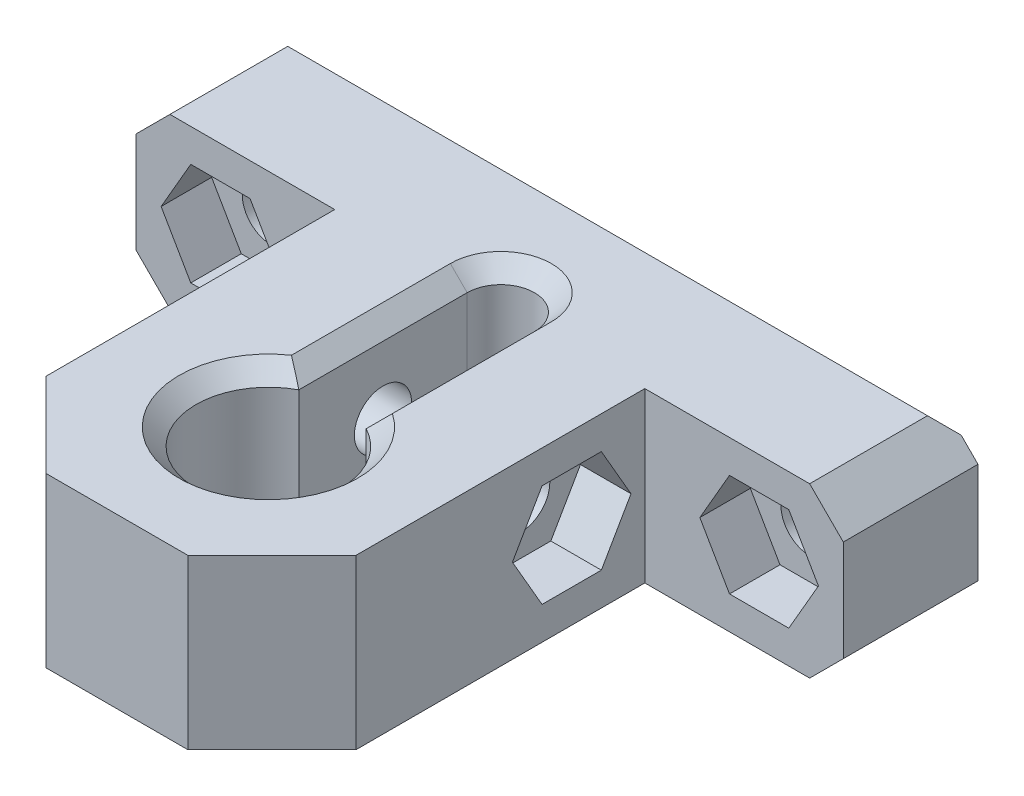
SolidWorks part; units mm, degrees
ref_plane "Front" through (0, 0, 0) normal (0, 0, 1) x (1, 0, 0)
ref_plane "Top" through (0, 0, 0) normal (0, 1, 0) x (1, 0, 0)
ref_plane "Right" through (0, 0, 0) normal (1, 0, 0) x (0, 0, -1)
sketch "Sketch1" plane through (0, 0, 0) normal (0, 1, 0) x (1, 0, 0)
  line L0 (-21, 0) -> (21, 0)
  line L1 (21, 0) -> (21, -8)
  line L2 (21, -8) -> (9.21, -8)
  line L3 (9.21, -8) -> (9.21, -30.15)
  line L4 (9.21, -30.15) -> (-9.21, -30.15)
  line L5 (-9.21, -30.15) -> (-9.21, -8)
  line L6 (-9.21, -8) -> (-21, -8)
  line L7 (-21, -8) -> (-21, 0)
  line L8 (0, 3.4386) -> (0, -31.4754) construction
  line L9 (-2, -7.3434) -> (-2, -17.3434)
  line L10 (2, -7.3434) -> (2, -17.3434)
  arc A0 (-2, -17.3434) -> (2, -17.3434) centre (0, -21.15) ccw
  arc A1 (-2, -7.3434) -> (2, -7.3434) centre (0, -7.3434) cw
  dimension "D2" = 8.6
  dimension "D4" = 9
  dimension "D1" = 42
  dimension "D3" = 30.15
  dimension "D5" = 8
  dimension "D6" = 4
  dimension "D7" = 10
  dimension "D8" = 18.42
extrude "Boss-Extrude1" add sketch "Sketch1" along normal blind 10
chamfer "Chamfer1" distance 5 angle 45 2 edges at (-9.21, 5, 30.15) (9.21, 5, 30.15)
chamfer "Chamfer2" distance 2 angle 45 4 edges at (21, 0, 4) (21, 10, 4) (-21, 0, 4) (-21, 10, 4)
chamfer "Chamfer3" distance 1 angle 45 10 edges at (2, 0, 12.3434) (0, 0, 5.3434) (0, 0, 25.45) (-2, 0, 12.3434) (2, 10, 12.3434) (0, 10, 5.3434) (0, 10, 25.45) (-2, 10, 12.3434) (0, 0, 0) (0, 10, 0)
sketch "Sketch2" plane through (9.21, 0, 0) normal (1, 0, 0) x (0, 0, -1)
  line L1 (-10.5825, 1.95) -> (-8.8216, 5)
  line L2 (-8.8216, 5) -> (-10.5825, 8.05)
  line L3 (-10.5825, 8.05) -> (-14.1043, 8.05)
  line L4 (-14.1043, 8.05) -> (-15.8653, 5)
  line L5 (-15.8653, 5) -> (-14.1043, 1.95)
  line L6 (-14.1043, 1.95) -> (-10.5825, 1.95)
  line L7 (-25.15, 10) -> (-8, 10) construction
  line L8 (-12.3434, 10) -> (-12.3434, 0) construction
  line L9 (-25.15, 0) -> (-8, 0) construction
  circle A0 centre (-12.3434, 5) radius 3.05 construction
  dimension "D1" = 6.1
extrude "Cut-Extrude1" cut sketch "Sketch2" against normal blind 3
hole_wizard "CBORE for M3 Hex Socket Head Cap Screw1" positions "Sketch5" profile "Sketch6" counterbore size "M3" standard "DIN" end condition through all
sketch "Sketch5" plane through (-9.21, 0, 0) normal (-1, 0, 0) x (0, 0, 1)
  line L1 (12.3434, 11.9144) -> (12.3434, -1.7687) construction
  line L5 (10.459, 5) -> (12.6378, 5) construction
  point P0 (12.3434, 5)
sketch "Sketch6" plane through (-9.21, 5, 12.3434) normal (0, 1, 0) x (0, 0, 1)
  line L0 (0, 0) -> (0, 30.21)
  line L1 (0, 30.21) -> (1.7, 30.21)
  line L3 (1.7, 30.21) -> (1.7, 3.4)
  line L4 (3.25, 3.4) -> (1.7, 3.4)
  line L5 (3.25, 3.4) -> (3.25, 0.025)
  line L6 (3.25, 0.025) -> (3.275, 0)
  line L7 (3.275, 0) -> (0, 0)
  line L8 (-3.25, 0.025) -> (-3.275, 0) construction
  line L11 (0, -6.35) -> (0, 107.95) construction
  dimension "Thru Hole Dia." = 3.4
  dimension "Thru Hole Depth" = 30.21
  dimension "C'Bore Dia." = 6.5
  dimension "C'Bore Depth" = 3.4
  dimension "Near C'Sink Dia." = 6.55
  dimension "Near C'Sink Angle" = 90
hole_wizard "M3 Clearance Hole1" positions "Sketch11" profile "Sketch10" hole size "M3" standard "DIN" end condition through all
sketch "Sketch11" plane through (0, 0, 0) normal (0, 0, -1) x (-1, 0, 0)
  line L2 (18.9892, 5) -> (11.5744, 5) construction
  line L4 (-19, 10) -> (19, 10) construction
  line L5 (19, 0) -> (-19, 0) construction
  line L6 (0, 12.2377) -> (0, -3.0724) construction
  point P0 (16, 5)
  point P20 (-16, 5)
  dimension "D1" = 32
sketch "Sketch10" plane through (-16, 5, 0) normal (1, 0, 0) x (0, 1, 0)
  line L0 (0, 0) -> (0, 30.15)
  line L1 (0, 30.15) -> (1.7, 30.15)
  line L2 (1.7, 30.15) -> (1.7, 0)
  line L5 (1.7, 0) -> (0, 0)
  line L11 (0, -6.35) -> (0, 107.95) construction
  dimension "Thru Hole Dia." = 3.4
  dimension "Thru Hole Depth" = 30.15
sketch "Sketch9" plane through (0, 0, 8) normal (0, 0, -1) x (-1, 0, 0)
  line L0 (0, 13.8123) -> (0, -4.7083) construction
  line L1 (17.7609, 1.95) -> (19.5218, 5)
  line L2 (19.5218, 5) -> (17.7609, 8.05)
  line L3 (17.7609, 8.05) -> (14.2391, 8.05)
  line L4 (14.2391, 8.05) -> (12.4782, 5)
  line L5 (12.4782, 5) -> (14.2391, 1.95)
  line L6 (14.2391, 1.95) -> (17.7609, 1.95)
  line L7 (-14.2391, 1.95) -> (-17.7609, 1.95)
  line L8 (-12.4782, 5) -> (-14.2391, 1.95)
  line L9 (-14.2391, 8.05) -> (-12.4782, 5)
  line L10 (-17.7609, 8.05) -> (-14.2391, 8.05)
  line L11 (-19.5218, 5) -> (-17.7609, 8.05)
  line L12 (-17.7609, 1.95) -> (-19.5218, 5)
  line L14 (20, 9) -> (-20, 9) construction
  circle A0 centre (16, 5) radius 3.05 construction
  circle A1 centre (-16, 5) radius 3.05 construction
  circle A2 centre (16, 5) radius 1.7 construction
  dimension "D1" = 6.1
extrude "Cut-Extrude2" cut sketch "Sketch9" along normal blind 3
